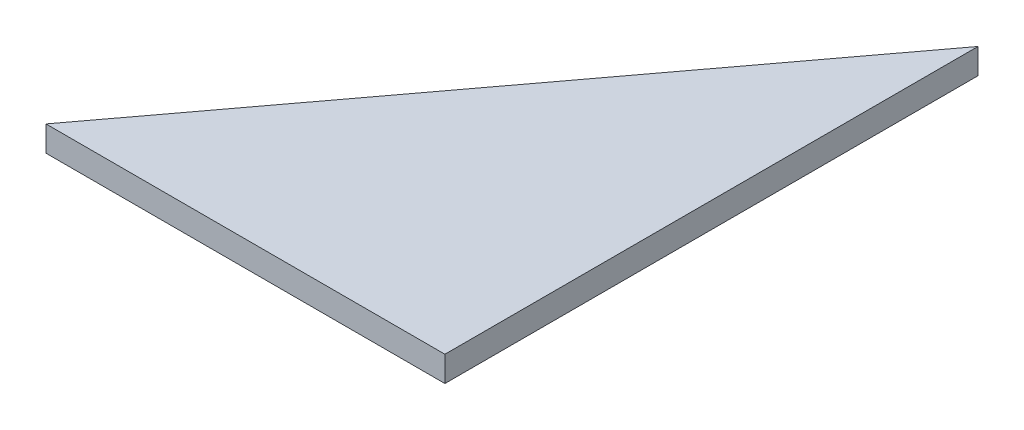
SolidWorks part; units mm, degrees
ref_plane "Front Plane" through (0, 0, 0) normal (0, 0, 1) x (1, 0, 0)
ref_plane "Top Plane" through (0, 0, 0) normal (0, 1, 0) x (1, 0, 0)
ref_plane "Right Plane" through (0, 0, 0) normal (1, 0, 0) x (0, 0, -1)
sketch "Sketch2" plane through (0, 0, 0) normal (0, 1, 0) x (1, 0, 0)
  line L0 (-39.7834, -4.8486) -> (15.2166, -4.8486)
  line L1 (15.2166, -4.8486) -> (15.2166, 68.6514)
  line L2 (15.2166, 68.6514) -> (-39.7834, -4.8486)
extrude "Boss-Extrude1" add sketch "Sketch2" along normal blind 3.5
